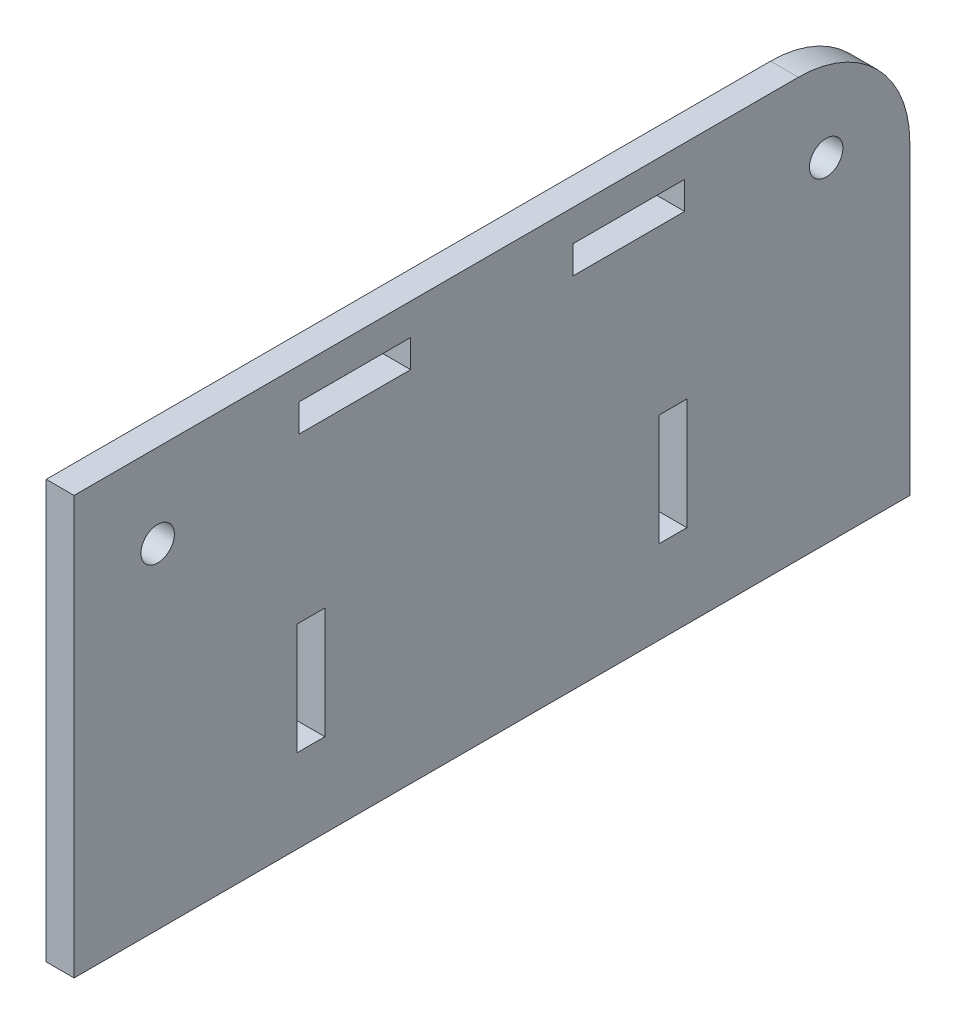
SolidWorks part; units mm, degrees
ref_plane "Front Plane" through (0, 0, 0) normal (0, 0, 1) x (1, 0, 0)
ref_plane "Top Plane" through (0, 0, 0) normal (0, 1, 0) x (1, 0, 0)
ref_plane "Right Plane" through (0, 0, 0) normal (1, 0, 0) x (0, 0, -1)
sketch "Sketch1" plane through (0, 0, 0) normal (1, 0, 0) x (0, 0, -1)
  line L1 (-105.3919, -37.5107) -> (44.6167, -37.5107)
  line L2 (44.6167, -37.5107) -> (44.6167, 17.5107)
  line L3 (24.6167, 37.5107) -> (-105.3919, 37.5107)
  line L4 (4.6053, -2.5007) -> (4.6053, -22.5064)
  line L5 (4.6053, -22.5064) -> (-0.3962, -22.5064)
  line L6 (-0.3962, -22.5064) -> (-0.3962, -2.5007)
  line L7 (-0.3962, -2.5007) -> (4.6053, -2.5007)
  line L8 (-15.7942, 31.8532) -> (-15.7942, 26.8517)
  line L9 (4.2115, 31.8532) -> (-15.7942, 31.8532)
  line L10 (-15.7942, 26.8517) -> (4.2115, 26.8517)
  line L11 (4.2115, 26.8517) -> (4.2115, 31.8532)
  line L21 (-64.9867, 26.8517) -> (-64.9867, 31.8532)
  line L23 (-44.981, 26.8517) -> (-64.9867, 26.8517)
  line L24 (-64.9867, 31.8532) -> (-44.981, 31.8532)
  line L25 (-44.981, 31.8532) -> (-44.981, 26.8517)
  line L26 (-60.3791, -2.5007) -> (-65.3805, -2.5007)
  line L27 (-60.3791, -22.5064) -> (-60.3791, -2.5007)
  line L28 (-65.3805, -22.5064) -> (-60.3791, -22.5064)
  line L29 (-65.3805, -2.5007) -> (-65.3805, -22.5064)
  line L30 (-105.3919, -37.5107) -> (-105.3919, 37.5107)
  circle A0 centre (29.6124, 22.5064) radius 3.0009
  circle A2 centre (-90.3876, 22.5064) radius 3.0009
  arc A3 (24.6167, 37.5107) -> (44.6167, 17.5107) centre (24.6167, 17.5107) cw
  dimension "D2" = 20
  dimension "D1" = 120
extrude "Boss-Extrude1" add sketch "Sketch1" along normal blind 5
